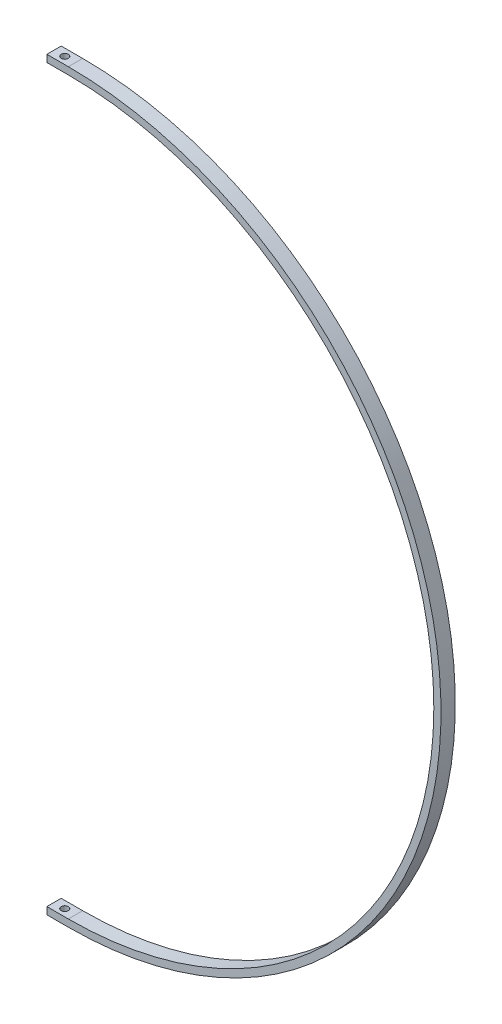
SolidWorks part; units mm, degrees
ref_plane "Front Plane" through (0, 0, 0) normal (0, 0, 1) x (1, 0, 0)
ref_plane "Top Plane" through (0, 0, 0) normal (0, 1, 0) x (1, 0, 0)
ref_plane "Right Plane" through (0, 0, 0) normal (1, 0, 0) x (0, 0, -1)
ref_axis "Axis3" through (0, 0, -195.3141) along (0, 0, 1)
sketch "Sketch1" plane through (0, 0, 0) normal (1, 0, 0) x (0, 0, -1)
  line L0 (0, 233.6432) -> (0, -233.6432) construction
  line L1 (-6.35, 330.2) -> (6.35, 330.2)
  line L2 (-6.35, 330.2) -> (-6.35, 323.85)
  line L3 (-6.35, 323.85) -> (6.35, 323.85)
  line L4 (6.35, 330.2) -> (6.35, 323.85)
  line L5 (0, 323.85) -> (0, 330.2) construction
  line L6 (-6.35, 327.025) -> (6.35, 327.025) construction
  point P0 (0, 327.025)
  point P9 (0, 0)
  dimension "D1" = 12.7
  dimension "D2" = 6.35
  dimension "D3" = 323.85
extrude "Boss-Extrude1" add sketch "Sketch1" against normal blind 19.05 contours L2 L1 L4 L3
sketch "Sketch2" plane through (0, 330.2, 0) normal (0, 1, 0) x (1, 0, 0)
  line L2 (0, 0) -> (-19.05, 0) construction
  line L3 (0, -6.35) -> (0, 6.35) construction
  line L4 (-19.05, -6.35) -> (-19.05, 6.35) construction
  circle A0 centre (-9.525, 0) radius 3.175
  dimension "D1" = 6.35
  dimension "D2" = 9.525
extrude "Cut-Extrude1" cut sketch "Sketch2" against normal blind 19.05 contours A0
sketch "Sketch9" plane through (0, 0, 0) normal (1, 0, 0) x (0, 0, -1)
  line L1 (-6.35, 323.85) -> (6.35, 323.85)
  line L2 (-6.35, 323.85) -> (-6.35, 330.2)
  line L3 (-6.35, 330.2) -> (6.35, 330.2)
  line L4 (6.35, 323.85) -> (6.35, 330.2)
  line L5 (0, 330.2) -> (0, 323.85) construction
  line L6 (-6.35, 327.025) -> (6.35, 327.025) construction
  point P220 (0, 327.025)
revolve "Revolve1" add sketch "Sketch9" angle 90 about axis through (0, 0, -195.3141) along (0, 0, 1)
mirror "Mirror2" about plane through (0, 0, 0) normal (0, 1, 0) of bodies 106
